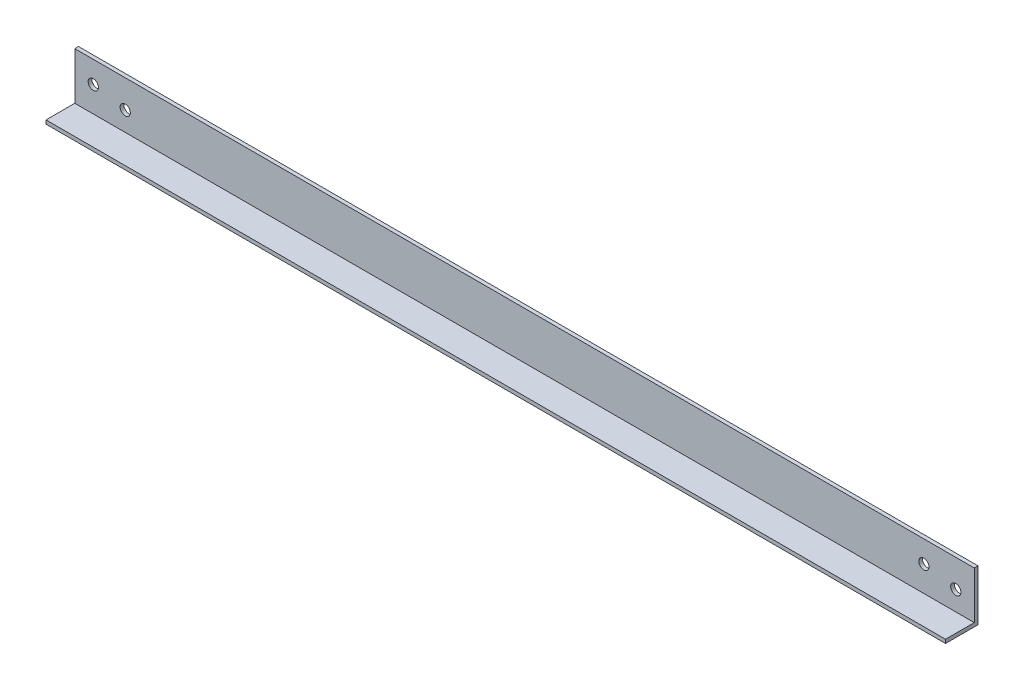
SolidWorks part; units mm, degrees
ref_plane "前视基准面" through (0, 0, 0) normal (0, 0, 1) x (1, 0, 0)
ref_plane "上视基准面" through (0, 0, 0) normal (0, 1, 0) x (1, 0, 0)
ref_plane "右视基准面" through (0, 0, 0) normal (1, 0, 0) x (0, 0, -1)
sketch "草图1" plane through (0, 0, 0) normal (0, 0, 1) x (1, 0, 0)
  line L1 (0, 0) -> (1938, 0)
  line L2 (0, 0) -> (0, 110)
  line L3 (0, 110) -> (1938, 110)
  line L4 (1938, 0) -> (1938, 110)
  dimension "D1" = 1938
  dimension "D2" = 110
extrude "拉伸3" add sketch "草图1" along normal blind 8
sketch "草图2" plane through (0, 0, 8) normal (0, 0, 1) x (1, 0, 0)
  line L1 (0, 0) -> (1938, 0)
  line L2 (0, 0) -> (0, 8)
  line L3 (0, 8) -> (1938, 8)
  line L4 (1938, 0) -> (1938, 8)
  dimension "D1" = 1938
  dimension "D2" = 8
extrude "拉伸4" add sketch "草图2" along normal blind 62
sketch "草图4" plane through (0, 0, 0) normal (0, 0, -1) x (-1, 0, 0)
  line L0 (0, 0) -> (-1938, 0) construction
  circle A0 centre (-1898.1569, 50) radius 11
  circle A1 centre (-1829.3607, 62.9203) radius 11
  circle A2 centre (-108.6842, 50) radius 11
  circle A3 centre (-39.888, 62.9203) radius 11
  point P10 (-969, 0)
  dimension "D1" = 12.9203
  dimension "D2" = 69.9989
  dimension "D3" = 69.9989
  dimension "D4" = 50
  dimension "D5" = 1858.2688
  dimension "D6" = 929.1569
extrude "切除-拉伸1" cut sketch "草图4" against normal through all
